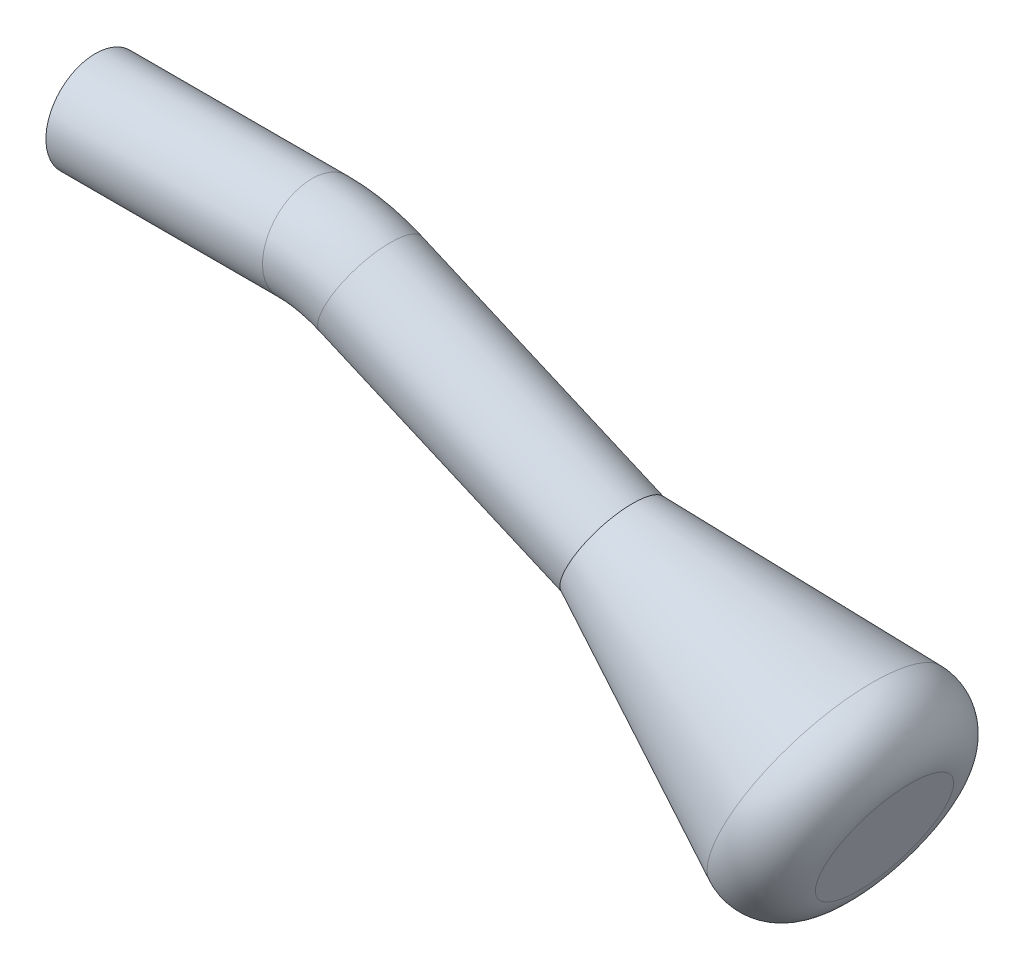
SolidWorks part; units mm, degrees
material "AISI 1020 Сталь, холоднокатаная"
ref_plane "Спереди" through (0, 0, 0) normal (0, 0, 1) x (1, 0, 0)
ref_plane "Сверху" through (0, 0, 0) normal (0, 1, 0) x (1, 0, 0)
ref_plane "Справа" through (0, 0, 0) normal (1, 0, 0) x (0, 0, -1)
sketch "Эскиз1" plane through (0, 0, 0) normal (0, 0, 1) x (1, 0, 0)
  line L0 (0, 0) -> (21.9586, 0)
  line L1 (27.9151, -1.2334) -> (80, -23.7694)
  line L2 (27.9151, -1.2334) -> (21.9586, -15) construction
  line L3 (21.9586, -15) -> (21.9586, 0) construction
  line L4 (21.9586, 0) -> (27.9151, -1.2334) construction
  line L5 (21.9586, -15) -> (25, -0.3116) construction
  arc A0 (21.9586, 0) -> (27.9151, -1.2334) centre (21.9586, -15) cw
  point P9 (21.9586, 0)
  dimension "D1" = 15
  dimension "D2" = 25
  dimension "D3" = 80
sketch "Эскиз2" plane through (0, 0, 0) normal (1, 0, 0) x (0, 0, -1)
  circle A0 centre (0, 0) radius 5
  dimension "D1" = 10
sweep "По траектории1" add profiles "Эскиз2" path "Эскиз1"
ref_plane "Плоскость1" through (48.5143, -20.9911, 0) normal (0.9178, -0.3971, 0) x (0, 0, -1)
sketch "Эскиз4" plane through (48.5143, -20.9911, 0) normal (0.9178, -0.3971, 0) x (0, 0, -1)
  circle A1 centre (0, 9.9532) radius 3
  circle A2 centre (0, 9.9532) radius 5 construction
  dimension "D1" = 6
extrude "Вырез-Вытянуть1" cut sketch "Эскиз4" along normal through all flip side to cut
sketch "Эскиз5" plane through (76.0476, -32.9042, 0) normal (0.9178, -0.3971, 0) x (0, 0, -1)
  circle A1 centre (0, 9.9532) radius 3
  circle A2 centre (0, 9.9532) radius 3
  dimension "D1" = 0
extrude "Вырез-Вытянуть2" cut sketch "Эскиз5" against normal blind 10
sketch "Эскиз6" plane through (48.5143, -20.9911, 0) normal (0.9178, -0.3971, 0) x (0, 0, -1)
  circle A0 centre (0, 9.9532) radius 5 construction
  circle A1 centre (0, 9.9532) radius 5
extrude "Бобышка-Вытянуть1" add sketch "Эскиз6" along normal blind 30 draft 15 separate body
fillet "Скругление1" radius 5 1 edges at (85.1776, -11.803, 0)
sketch "Эскиз7" plane through (48.5143, -20.9911, 0) normal (-0.9178, 0.3971, 0) x (0, 0, 1)
  circle A0 centre (0, 9.9532) radius 3
  circle A1 centre (0, 9.9532) radius 5 construction
  dimension "D1" = 6
extrude "Вырез-Вытянуть3" cut sketch "Эскиз7" against normal blind 22
sketch "Эскиз8" [suppressed] plane through (0, 0, 0) normal (0, 0, 1) x (1, 0, 0)
  line L1 (49.2768, -4.174) -> (84.9099, -4.174)
  line L2 (49.2768, -4.174) -> (49.2768, -33.9621)
  line L3 (49.2768, -33.9621) -> (84.9099, -33.9621)
  line L4 (84.9099, -4.174) -> (84.9099, -33.9621)
extrude "Вырез-Вытянуть4" [suppressed] cut sketch "Эскиз8" along normal through all
